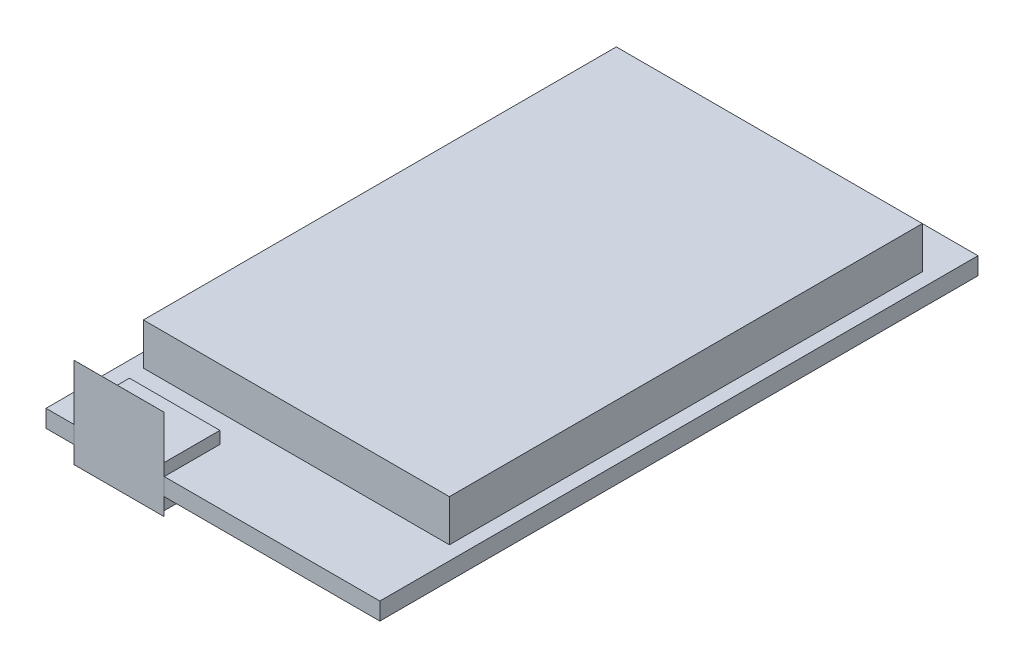
SolidWorks part; units mm, degrees
ref_plane "Front Plane" through (0, 0, 0) normal (0, 0, 1) x (1, 0, 0)
ref_plane "Top Plane" through (0, 0, 0) normal (0, 1, 0) x (1, 0, 0)
ref_plane "Right Plane" through (0, 0, 0) normal (1, 0, 0) x (0, 0, -1)
sketch "Sketch1" plane through (0, 0, 0) normal (0, 1, 0) x (1, 0, 0)
  line L1 (-12, 21.5) -> (12, 21.5)
  line L2 (-12, 21.5) -> (-12, -21.5)
  line L3 (-12, -21.5) -> (12, -21.5)
  line L4 (12, 21.5) -> (12, -21.5)
  line L5 (-12, 21.5) -> (12, -21.5) construction
  line L6 (-12, -21.5) -> (12, 21.5) construction
  point P0 (0, 0)
  dimension "D1" = 43
  dimension "D2" = 24
extrude "PCB" add sketch "Sketch1" along normal blind 1.25
sketch "Sketch2" plane through (0, 1.25, 0) normal (0, 1, 0) x (1, 0, 0)
  line L0 (-12, -21.5) -> (12, -21.5) construction
  line L1 (-11, 18.5) -> (11, 18.5)
  line L2 (-11, 18.5) -> (-11, -15.5)
  line L3 (-11, -15.5) -> (11, -15.5)
  line L4 (11, 18.5) -> (11, -15.5)
  line L5 (-11, 18.5) -> (11, -15.5) construction
  line L6 (-11, -15.5) -> (11, 18.5) construction
  point P0 (0, 1.5)
  dimension "D1" = 34
  dimension "D2" = 22
  dimension "D3" = 6
extrude "RF Casing" add sketch "Sketch2" along normal blind 3
sketch "Sketch3" plane through (0, 0, 21.5) normal (0, 0, 1) x (1, 0, 0)
  line L0 (-12, 1.25) -> (-12, 0) construction
  line L1 (-10, 5.25) -> (-3.5, 5.25)
  line L2 (-10, 5.25) -> (-10, -1.25)
  line L3 (-10, -1.25) -> (-3.5, -1.25)
  line L4 (-3.5, 5.25) -> (-3.5, -1.25)
  line L5 (-10, 5.25) -> (-3.5, -1.25) construction
  line L6 (-10, -1.25) -> (-3.5, 5.25) construction
  line L7 (-11, 1.25) -> (11, 1.25) construction
  point P0 (-6.75, 2)
  dimension "D1" = 2
  dimension "D2" = 6.5
  dimension "D3" = 2.5
extrude "RF Connector Back" add sketch "Sketch3" along normal blind 0.001
sketch "Sketch4" plane through (0, 0, 21.501) normal (0, 0, 1) x (1, 0, 0)
  line L0 (-10, 5.25) -> (-3.5, -1.25) construction
  circle A0 centre (-6.75, 2) radius 3
  point P11 (-6.75, 2)
  dimension "D1" = 6
extrude "RF Connector Threads" [suppressed] add sketch "Sketch4" along normal blind 11
sketch "Sketch5" plane through (0, 0, 21.5) normal (0, 0, -1) x (-1, 0, 0)
  line L0 (3.5, 5.25) -> (10, 5.25) construction
  line L1 (3.5, 2.125) -> (10, 2.125)
  line L2 (3.5, 2.125) -> (3.5, -0.875)
  line L3 (3.5, -0.875) -> (10, -0.875)
  line L4 (10, 2.125) -> (10, -0.875)
  line L5 (3.5, 2.125) -> (10, -0.875) construction
  line L6 (3.5, -0.875) -> (10, 2.125) construction
  line L7 (3.5, 1.25) -> (3.5, 5.25) construction
  line L8 (12, 1.25) -> (12, 0) construction
  point P0 (6.75, 0.625)
  point P7 (6.75, 5.25)
  point P12 (12, 0.625)
  dimension "D1" = 3
extrude "RF Connector Pins" add sketch "Sketch5" along normal blind 4
